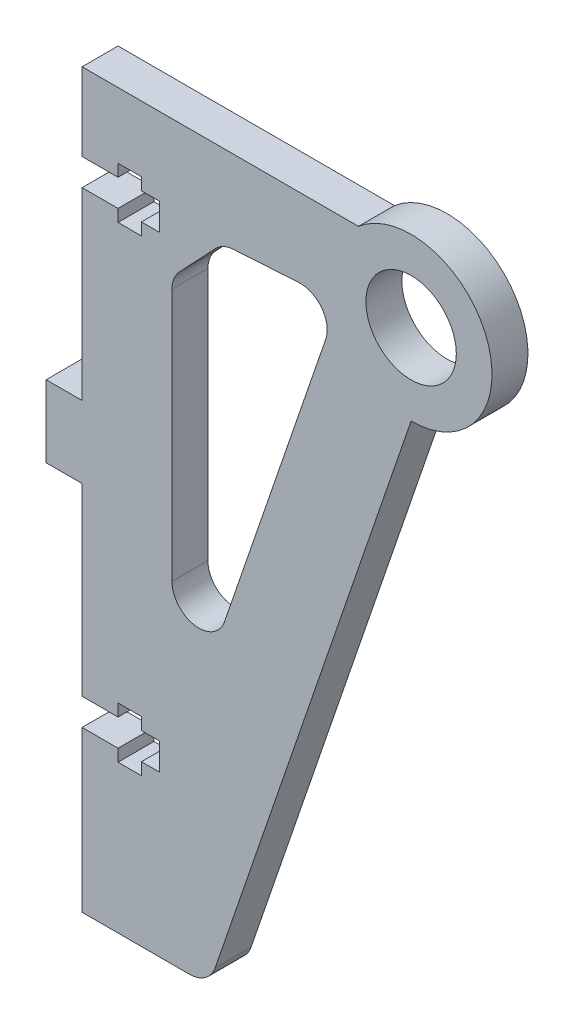
SolidWorks part; units mm, degrees
ref_plane "前视基准面" through (0, 0, 0) normal (0, 0, 1) x (1, 0, 0)
ref_plane "上视基准面" through (0, 0, 0) normal (0, 1, 0) x (1, 0, 0)
ref_plane "右视基准面" through (0, 0, 0) normal (1, 0, 0) x (0, 0, -1)
sketch "草图1" plane through (0, 0, 0) normal (0, 0, 1) x (1, 0, 0)
  line L0 (0, 0) -> (-96.1714, 0) construction
  line L1 (0, 0) -> (-41.1584, 71.2884) construction
  line L3 (-31.5, 38.9711) -> (-60.7565, 0) construction
  line L9 (-22.5, 38.9711) -> (-59.1, 38.9711) construction
  line L10 (-59.1, 38.9711) -> (-59.1, -35.646)
  line L11 (-59.1, -35.646) -> (-47.1428, -35.646)
  line L14 (-44.305, -33.6191) -> (-22.5, 29.9711)
  line L16 (-59.1, 38.9711) -> (-59.1, 42.8144)
  line L19 (-42.2751, 36.639) -> (-35.014, 37.0788)
  line L20 (-43.2622, 0.252) -> (-31.9948, 33.1112)
  line L21 (-49.1, 36.2256) -> (-30.5415, 37.3497) construction
  line L22 (-49.1, 29.3882) -> (-49.1, 1.2251)
  line L23 (-48.2845, 31.4444) -> (-44.2782, 35.7007)
  line L25 (-49.1, 36.2256) -> (-49.1, -16.7729) construction
  line L26 (-49.1, -16.7729) -> (-30.5415, 37.3497) construction
  line L27 (-49.1, -16.7729) -> (-49.1, -16.7729) construction
  line L28 (-49.1, 36.2256) -> (-49.1, 36.2256) construction
  line L29 (-59.1, -35.646) -> (-45, -35.646) construction
  line L30 (-45, -35.646) -> (-22.5, 29.9711) construction
  line L31 (-59.1, 45.6382) -> (-24.571, 47.7296) construction
  line L32 (-59.1, 38.9711) -> (-59.1, 45.6382) construction
  line L33 (-56.2814, 45.809) -> (-59.1, 45.809)
  line L34 (-59.1, 45.809) -> (-59.1, 42.8144)
  line L35 (-56.2814, 45.809) -> (-28.3519, 45.809)
  circle A0 centre (0, 0) radius 45 construction
  circle A1 centre (-22.5, 38.9711) radius 5.03
  circle A2 centre (-22.5, 38.9711) radius 9 construction
  arc A7 (-42.2751, 36.639) -> (-44.2782, 35.7007) centre (-42.0937, 33.6445) ccw
  arc A9 (-49.1, 1.2251) -> (-43.2622, 0.252) centre (-46.1, 1.2251) ccw
  arc A11 (-31.9948, 33.1112) -> (-35.014, 37.0788) centre (-34.8326, 34.0843) ccw
  arc A12 (-30.5415, 37.3497) -> (-30.5415, 37.3497) centre (-30.5415, 37.3497) ccw construction
  arc A13 (-49.1, 29.3882) -> (-48.2845, 31.4444) centre (-46.1, 29.3882) cw
  arc A14 (-47.1428, -35.646) -> (-44.305, -33.6191) centre (-47.1428, -32.646) ccw
  arc A15 (-22.5, 29.9711) -> (-24.571, 47.7296) centre (-22.5, 38.9711) ccw construction
  arc A16 (-28.3519, 45.809) -> (-22.5, 29.9711) centre (-22.5, 38.9711) cw
  dimension "D1" = 60
  dimension "D2" = 10
  dimension "D3" = 3
  dimension "D4" = 3
  dimension "D5" = 3
  dimension "D6" = 3
extrude "凸台-拉伸1" add sketch "草图1" along normal blind 4 contours L3
sketch "草图2" plane through (0, 0, 4) normal (0, 0, 1) x (1, 0, 0)
  line L0 (-59.1, 5.0815) -> (-55.2701, 5.0815) construction
  line L1 (-59.1, 45.809) -> (-59.1, -35.646) construction
  line L14 (-59.1, 5.0815) -> (-59.1, -16.3374) construction
  line L15 (-59.1, -16.3374) -> (-55.2701, -16.3374) construction
  line L16 (-59.1, -14.8374) -> (-55.1, -14.8374)
  line L17 (-55.1, -14.8374) -> (-55.1, -13.4874)
  line L18 (-55.1, -13.4874) -> (-52.5, -13.4874)
  line L19 (-52.5, -13.4874) -> (-52.5, -14.8374)
  line L20 (-52.5, -14.8374) -> (-50.5, -14.8374)
  line L21 (-50.5, -14.8374) -> (-50.5, -17.8374)
  line L22 (-52.5, -17.8374) -> (-50.5, -17.8374)
  line L23 (-52.5, -19.1874) -> (-52.5, -17.8374)
  line L24 (-55.1, -19.1874) -> (-52.5, -19.1874)
  line L25 (-55.1, -17.8374) -> (-55.1, -19.1874)
  line L26 (-59.1, -17.8374) -> (-55.1, -17.8374)
  line L27 (-59.1, 5.0815) -> (-59.1, 35.6626) construction
  line L28 (-59.1, 35.6626) -> (-55.2701, 35.6626) construction
  line L29 (-59.1, 37.1626) -> (-55.1, 37.1626)
  line L30 (-55.1, 37.1626) -> (-55.1, 38.5126)
  line L31 (-55.1, 38.5126) -> (-52.5, 38.5126)
  line L32 (-52.5, 38.5126) -> (-52.5, 37.1626)
  line L33 (-52.5, 37.1626) -> (-50.5, 37.1626)
  line L34 (-50.5, 37.1626) -> (-50.5, 34.1626)
  line L35 (-52.5, 34.1626) -> (-50.5, 34.1626)
  line L36 (-52.5, 32.8126) -> (-52.5, 34.1626)
  line L37 (-55.1, 32.8126) -> (-52.5, 32.8126)
  line L38 (-55.1, 34.1626) -> (-55.1, 32.8126)
  line L39 (-59.1, 34.1626) -> (-55.1, 34.1626)
  line L40 (-59.1, -17.8374) -> (-59.1, -14.8374)
  line L41 (-59.1, 37.1626) -> (-59.1, 34.1626)
  point P15 (-50.5, 35.6626)
  point P28 (-50.5, -16.3374)
extrude "切除-拉伸1" cut sketch "草图2" against normal blind 4
sketch "草图4" plane through (-59.1, 0, 0) normal (-1, 0, 0) x (0, 0, 1)
  line L0 (4, 34.1626) -> (4, -14.8374) construction
  line L1 (4, 13.6594) -> (0, 13.6594)
  line L2 (4, 13.6594) -> (4, 5.6594)
  line L3 (4, 5.6594) -> (0, 5.6594)
  line L4 (0, 13.6594) -> (0, 5.6594)
  line L5 (0, 34.1626) -> (0, -14.8374) construction
extrude "凸台-拉伸2" add sketch "草图4" along normal blind 4
sketch "草图5" plane through (-59.1, 0, 0) normal (-1, 0, 0) x (0, 0, 1)
  line L0 (2, 37.1626) -> (2, 34.1626)
  line L1 (0, 37.1626) -> (4, 37.1626) construction
  line L2 (0, 34.1626) -> (4, 34.1626) construction
  circle A0 centre (2, 35.6626) radius 1.5
sketch "草图6" plane through (-59.1, 0, 0) normal (-1, 0, 0) x (0, 0, 1)
  line L0 (2, -14.8374) -> (2, -17.8374)
  line L1 (0, -14.8374) -> (4, -14.8374) construction
  line L2 (0, -17.8374) -> (4, -17.8374) construction
  circle A0 centre (2, -16.3374) radius 1.5
